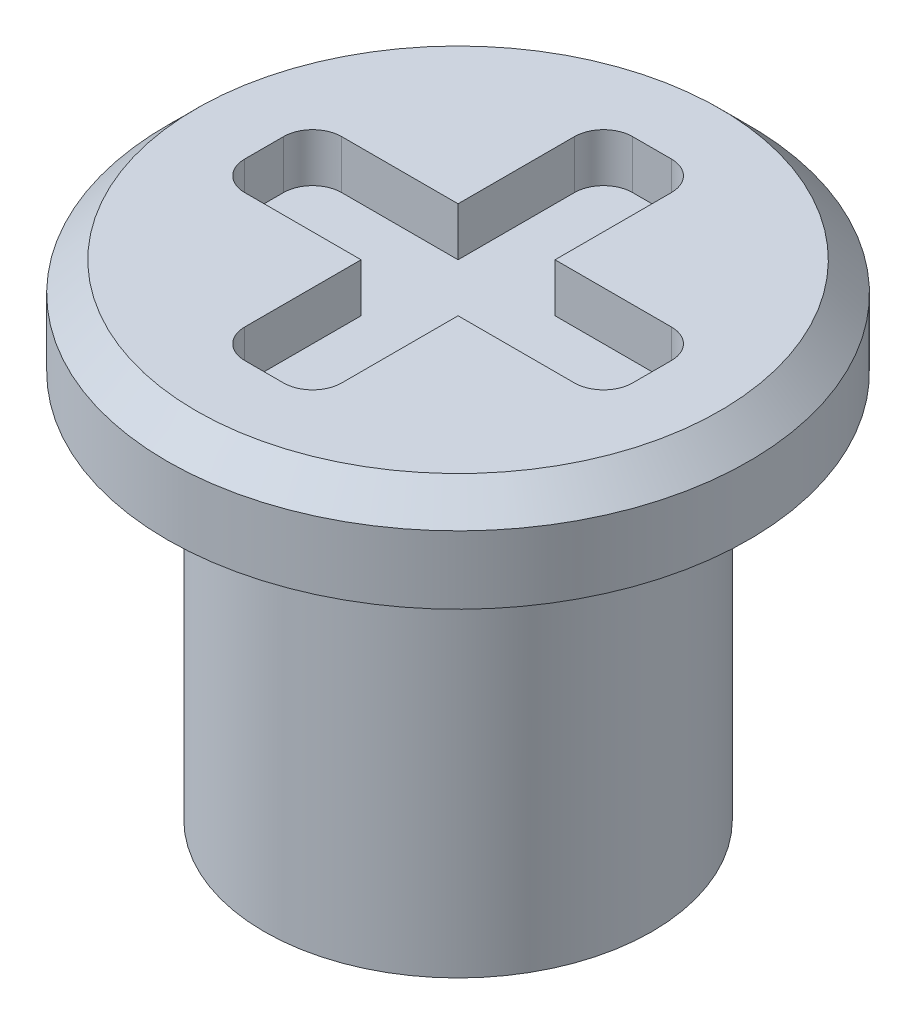
SolidWorks part; units mm, degrees
material "SS BS EN 10088-2 1.4301"
ref_plane "Front" through (0, 0, 0) normal (0, 0, 1) x (1, 0, 0)
ref_plane "Top" through (0, 0, 0) normal (0, 1, 0) x (1, 0, 0)
ref_plane "Right" through (0, 0, 0) normal (1, 0, 0) x (0, 0, -1)
sketch "Sketch1" plane through (0, 0, 0) normal (0, 1, 0) x (1, 0, 0)
  circle A0 centre (0, 0) radius 1.5
  dimension "D1" = 3
extrude "Boss-Extrude1" add sketch "Sketch1" along normal blind 0.5
sketch "Sketch2" plane through (0, 0.5, 0) normal (0, 1, 0) x (1, 0, 0)
  line L1 (-0.1, -1) -> (0.1, -1)
  line L2 (-0.25, -0.85) -> (-0.25, -0.25)
  line L3 (-0.1, 1) -> (0.1, 1)
  line L4 (0.25, -0.85) -> (0.25, -0.25)
  line L5 (-0.25, -1) -> (-0.2308, -0.9234) construction
  line L6 (-0.25, 1) -> (-0.2308, 0.9234) construction
  line L7 (-0.85, 0.25) -> (-0.25, 0.25)
  line L8 (-1, 0.1) -> (-1, -0.1)
  line L9 (-0.85, -0.25) -> (-0.25, -0.25)
  line L10 (1, 0.1) -> (1, -0.1)
  line L11 (-1, 0.25) -> (-0.9234, 0.2308) construction
  line L12 (-1, -0.25) -> (-0.9234, -0.2308) construction
  line L14 (-0.25, 0.25) -> (-0.25, 0.85)
  line L15 (0.2308, -0.9234) -> (0.25, -1) construction
  line L16 (0.2308, 0.9234) -> (0.25, 1) construction
  line L17 (0.25, 0.25) -> (0.25, 0.85)
  line L18 (0.9234, 0.2308) -> (1, 0.25) construction
  line L19 (0.9234, -0.2308) -> (1, -0.25) construction
  line L22 (0.25, 0.25) -> (0.85, 0.25)
  line L23 (0.25, -0.25) -> (0.85, -0.25)
  arc A0 (0.1, -1) -> (0.25, -0.85) centre (0.1, -0.85) ccw
  arc A1 (-0.1, -1) -> (-0.25, -0.85) centre (-0.1, -0.85) cw
  arc A2 (-1, -0.1) -> (-0.85, -0.25) centre (-0.85, -0.1) ccw
  arc A3 (-0.85, 0.25) -> (-1, 0.1) centre (-0.85, 0.1) ccw
  arc A4 (0.85, -0.25) -> (1, -0.1) centre (0.85, -0.1) ccw
  arc A5 (0.85, 0.25) -> (1, 0.1) centre (0.85, 0.1) cw
  arc A6 (-0.25, 0.85) -> (-0.1, 1) centre (-0.1, 0.85) cw
  arc A7 (0.1, 1) -> (0.25, 0.85) centre (0.1, 0.85) cw
  point P0 (0, 0)
  point P6 (0, 0)
  dimension "D3" = 0.15
  dimension "D1" = 0.5
  dimension "D2" = 2
extrude "Cut-Extrude1" cut sketch "Sketch2" against normal blind 0.25
chamfer "Chamfer1" distance 0.15 angle 45 1 edges at (0, 0.5, 1.5)
sketch "Sketch3" plane through (0, 0, 0) normal (0, -1, 0) x (1, 0, 0)
  circle A0 centre (0, 0) radius 1
  dimension "D1" = 2
extrude "Boss-Extrude2" add sketch "Sketch3" along normal blind 2
